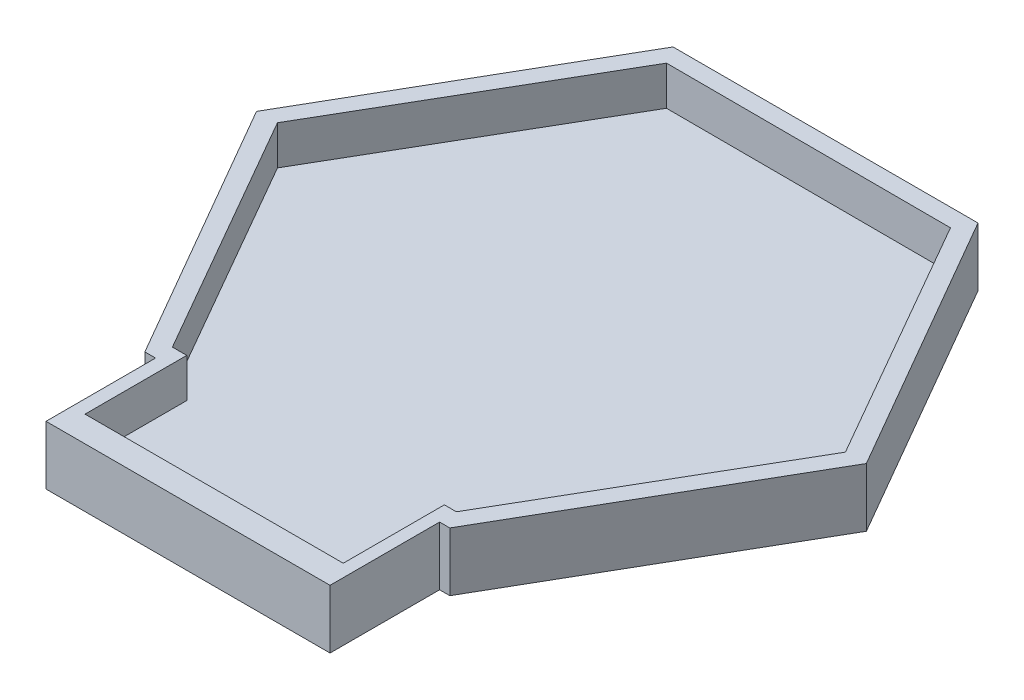
SolidWorks part; units mm, degrees
ref_plane "Front Plane" through (0, 0, 0) normal (0, 0, 1) x (1, 0, 0)
ref_plane "Top Plane" through (0, 0, 0) normal (0, 1, 0) x (1, 0, 0)
ref_plane "Right Plane" through (0, 0, 0) normal (1, 0, 0) x (0, 0, -1)
sketch "Sketch1" plane through (0, 0, 0) normal (0, 1, 0) x (1, 0, 0)
  line L1 (98.9867, 0) -> (49.4934, 85.725)
  line L2 (49.4934, 85.725) -> (-49.4934, 85.725)
  line L3 (-49.4934, 85.725) -> (-98.9867, 0)
  line L4 (-98.9867, 0) -> (-49.4934, -85.725)
  line L5 (-49.4934, -85.725) -> (49.4934, -85.725)
  line L6 (49.4934, -85.725) -> (98.9867, 0)
  line L7 (-46.0239, -85.725) -> (46.1781, -85.725)
  line L8 (-46.0239, -85.725) -> (-46.0239, -121.285)
  line L9 (-46.0239, -121.285) -> (46.1781, -121.285)
  line L10 (46.1781, -85.725) -> (46.1781, -121.285)
  circle A0 centre (0, 0) radius 85.725 construction
  dimension "D1" = 171.45
  dimension "D2" = 92.202
extrude "Boss-Extrude3" add sketch "Sketch1" along normal blind 19.05 contours L5 L6 L1 L2 L3 L4 | L10 L5 L8 L9
sketch "Sketch4" plane through (0, 19.05, 0) normal (0, 1, 0) x (1, 0, 0)
  line L1 (46.0117, -80.1149) -> (92.3874, -0.2101)
  line L2 (92.3874, -0.2101) -> (46.3756, 79.9047)
  line L3 (46.3756, 79.9047) -> (-46.0117, 80.1149)
  line L4 (-46.0117, 80.1149) -> (-92.3874, 0.2101)
  line L5 (-92.3874, 0.2101) -> (-46.3756, -79.9047)
  line L6 (-46.3756, -79.9047) -> (46.0117, -80.1149)
  line L7 (-41.7054, -79.9154) -> (42.1146, -79.9154)
  line L8 (-41.7054, -79.9154) -> (-41.7054, -112.9354)
  line L9 (-41.7054, -112.9354) -> (42.1146, -112.9354)
  line L10 (42.1146, -79.9154) -> (42.1146, -112.9354)
  circle A0 centre (0, 0) radius 80.01 construction
  dimension "D1" = 160.02
  dimension "D2" = 33.02
  dimension "D3" = 83.82
extrude "Cut-Extrude1" cut sketch "Sketch4" against normal blind 12.7 contours L10 L6 L8 L9
